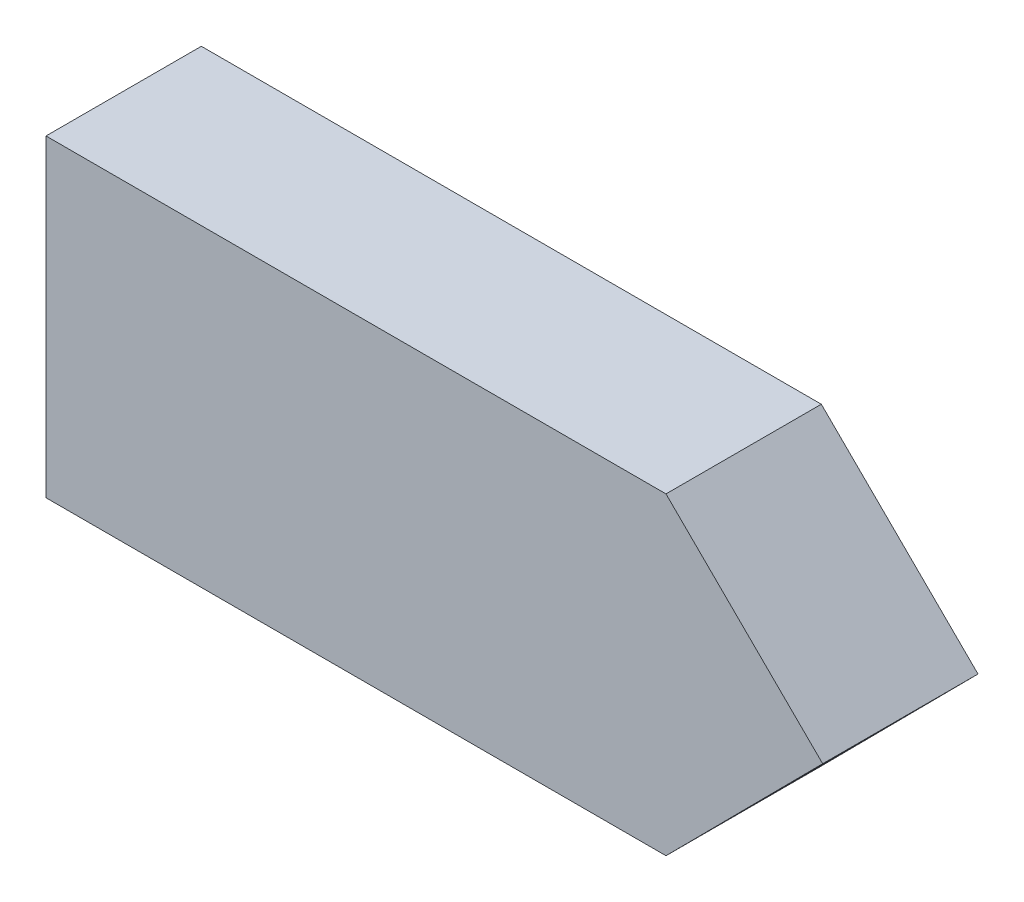
SolidWorks part; units mm, degrees
ref_plane "Front Plane" through (0, 0, 0) normal (0, 0, 1) x (1, 0, 0)
ref_plane "Top Plane" through (0, 0, 0) normal (0, 1, 0) x (1, 0, 0)
ref_plane "Right Plane" through (0, 0, 0) normal (1, 0, 0) x (0, 0, -1)
other "Configuration Table"
sketch "Sketch1" plane through (0, 0, 0) normal (0, 0, 1) x (1, 0, 0)
  line L0 (-60, 40) -> (-20.0864, 40)
  line L1 (-20.0864, 40) -> (-10, 30)
  line L2 (-10, 30) -> (-20.0864, 19.8264)
  line L3 (-20.0864, 19.8264) -> (-60, 19.8264)
  line L4 (-60, 19.8264) -> (-60, 40)
extrude "Boss-Extrude1" add sketch "Sketch1" along normal blind 10
